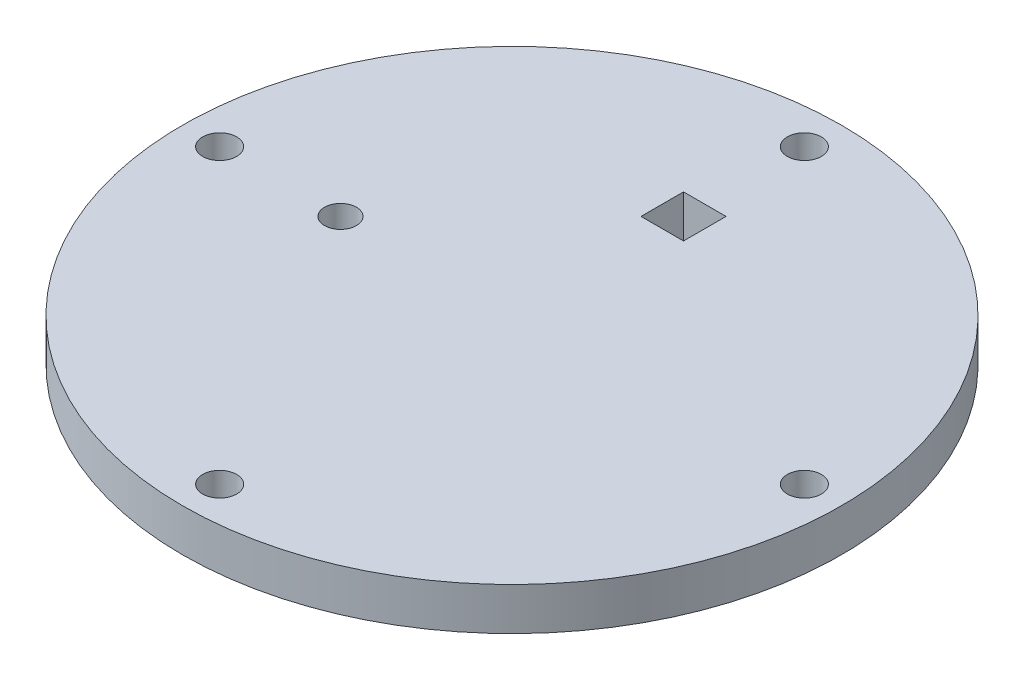
SolidWorks part; units mm, degrees
ref_plane "Front Plane" through (0, 0, 0) normal (0, 0, 1) x (1, 0, 0)
ref_plane "Top Plane" through (0, 0, 0) normal (0, 1, 0) x (1, 0, 0)
ref_plane "Right Plane" through (0, 0, 0) normal (1, 0, 0) x (0, 0, -1)
sketch "Sketch1" plane through (0, 0, 0) normal (0, 1, 0) x (1, 0, 0)
  circle A0 centre (0, 0) radius 31
extrude "Boss-Extrude1" add sketch "Sketch1" along normal blind 4
sketch "Sketch3" plane through (0, 4, 0) normal (0, 1, 0) x (1, 0, 0)
  circle A0 centre (0, 0) radius 27.5
hole_wizard "Ø3.2 (3.2) Diameter Hole1" positions "Sketch4" profile "Sketch5" hole size "Ø3.2" standard "ISO" end condition through all
sketch "Sketch4" plane through (0, 4, 0) normal (0, 1, 0) x (1, 0, 0)
  circle A0 centre (0, 0) radius 27.5 construction
  point P0 (-27.5, 0)
  point P4 (27.5, 0)
  point P6 (0, 27.5)
  point P8 (0, -27.5)
sketch "Sketch5" plane through (-27.5, 4, 0) normal (1, 0, 0) x (0, 0, 1)
  line L0 (0, 0) -> (0, 4)
  line L1 (0, 4) -> (1.6, 4)
  line L2 (1.6, 4) -> (1.6, 0)
  line L5 (1.6, 0) -> (0, 0)
  line L11 (0, -6.35) -> (0, 107.95) construction
  dimension "Thru Hole Dia." = 3.2
  dimension "Thru Hole Depth" = 4
sketch "Sketch6" plane through (0, 4, 0) normal (0, 1, 0) x (1, 0, 0)
  line L1 (-2, 18.135) -> (2, 18.135)
  line L2 (-2, 18.135) -> (-2, 14.135)
  line L3 (-2, 14.135) -> (2, 14.135)
  line L4 (2, 18.135) -> (2, 14.135)
  line L5 (-2, 18.135) -> (2, 14.135) construction
  line L6 (-2, 14.135) -> (2, 18.135) construction
  circle A0 centre (0, 0) radius 1
  circle A1 centre (0, 0) radius 16.135
  point P4 (0, 16.135)
  dimension "D1" = 4
  dimension "D2" = 4
hole_wizard "Ø3.0 (3) Diameter Hole1" positions "Sketch7" profile "Sketch8" hole size "Ø3.0" standard "ISO" end condition through all
sketch "Sketch7" plane through (0, 4, 0) normal (0, 1, 0) x (1, 0, 0)
  circle A0 centre (0, 0) radius 16.135 construction
  point P0 (-16.135, 0)
sketch "Sketch8" plane through (-16.135, 4, 0) normal (1, 0, 0) x (0, 0, 1)
  line L0 (0, 0) -> (0, 4)
  line L1 (0, 4) -> (1.5, 4)
  line L2 (1.5, 4) -> (1.5, 0)
  line L5 (1.5, 0) -> (0, 0)
  line L11 (0, -6.35) -> (0, 107.95) construction
  dimension "Thru Hole Dia." = 3
  dimension "Thru Hole Depth" = 4
extrude "Cut-Extrude2" cut sketch "Sketch6" against normal through all contours L1 L4 L3 L2
